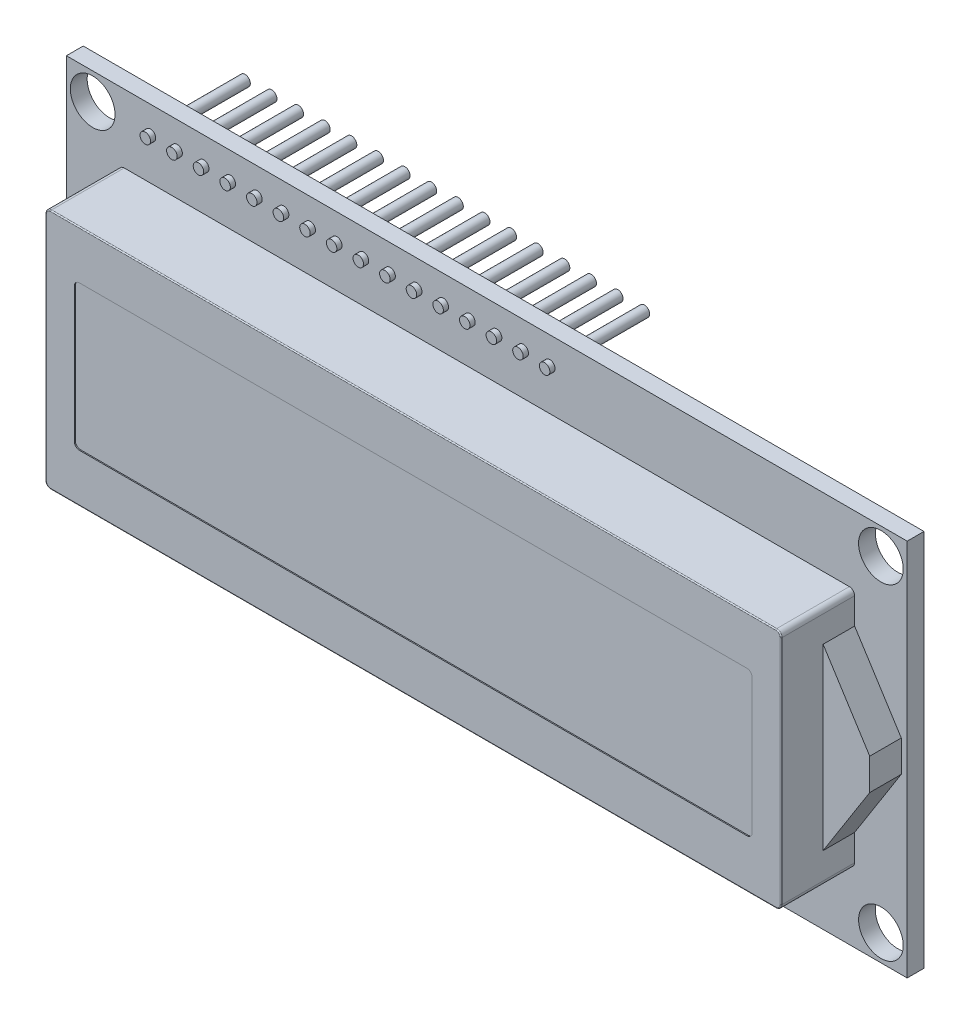
SolidWorks part; units mm, degrees
ref_plane "Alzado" through (0, 0, 0) normal (0, 0, 1) x (1, 0, 0)
ref_plane "Planta" through (0, 0, 0) normal (0, 1, 0) x (1, 0, 0)
ref_plane "Vista lateral" through (0, 0, 0) normal (1, 0, 0) x (0, 0, -1)
sketch "Croquis1" plane through (0, 0, 0) normal (0, 0, 1) x (1, 0, 0)
  line L1 (0, 0) -> (80, 0)
  line L2 (0, 0) -> (0, 36)
  line L3 (0, 36) -> (80, 36)
  line L4 (80, 0) -> (80, 36)
  circle A0 centre (2.5, 33.46) radius 2.125
  circle A1 centre (77.5, 33.51) radius 2.125
  circle A2 centre (77.5, 2.49) radius 2.125
  circle A3 centre (2.5, 2.49) radius 2.125
  circle A4 centre (8, 33.46) radius 0.5
  circle A5 centre (10.5333, 33.46) radius 0.5
  circle A6 centre (13.0667, 33.46) radius 0.5
  circle A7 centre (15.6, 33.46) radius 0.5
  circle A8 centre (18.1333, 33.46) radius 0.5
  circle A9 centre (20.6667, 33.46) radius 0.5
  circle A10 centre (23.2, 33.46) radius 0.5
  circle A11 centre (25.7333, 33.46) radius 0.5
  circle A12 centre (28.2666, 33.46) radius 0.5
  circle A13 centre (30.8, 33.46) radius 0.5
  circle A14 centre (33.3333, 33.46) radius 0.5
  circle A15 centre (35.8666, 33.46) radius 0.5
  circle A16 centre (38.4, 33.46) radius 0.5
  circle A17 centre (40.9333, 33.46) radius 0.5
  circle A18 centre (43.4666, 33.46) radius 0.5
  circle A19 centre (45.9999, 33.46) radius 0.5
  dimension "D3" = 4.25
  dimension "D7" = 1
  dimension "D1" = 80
  dimension "D2" = 36
  dimension "D5" = 2.5
  dimension "D6" = 8
  dimension "D8" = 2.54
  dimension "D9" = 16
extrude "Saliente-Extruir1" add sketch "Croquis1" along normal blind 1.6
sketch "Croquis2" plane through (0, 0, 1.6) normal (0, 0, 1) x (1, 0, 0)
  line L0 (0, 36) -> (0, 0) construction
  line L1 (5, 29.5) -> (75, 29.5)
  line L2 (5, 29.5) -> (5, 6.5)
  line L3 (5, 6.5) -> (75, 6.5)
  line L4 (75, 29.5) -> (75, 6.5)
  line L5 (80, 36) -> (0, 36) construction
  dimension "D1" = 70
  dimension "D2" = 5
  dimension "D3" = 6.5
  dimension "D4" = 23
extrude "Saliente-Extruir2" add sketch "Croquis2" along normal blind 7
sketch "Croquis3" plane through (0, 0, 1.6) normal (0, 0, 1) x (1, 0, 0)
  line L0 (75, 26.5) -> (79.4378, 19.5)
  line L1 (75, 6.5) -> (75, 29.5) construction
  line L2 (79.4378, 19.5) -> (79.4378, 16.5)
  line L3 (79.4378, 16.5) -> (75, 9.5)
  line L4 (75, 26.5) -> (75, 9.5)
  line L5 (75, 9.5) -> (74.9994, 9.3543)
  line M27 (75, 29.5) -> (75, 6.5)
  dimension "D1" = 3
  dimension "D2" = 3
  dimension "D3" = 7
  dimension "D4" = 7
extrude "Saliente-Extruir3" add sketch "Croquis3" along normal blind 3 contours L3 L2 L0 M27
sketch "Croquis4" plane through (0, 0, 1.6) normal (0, 0, 1) x (1, 0, 0)
  text T0 "1                                                 16" font "Century Gothic" height in points 8
sketch "Croquis6" plane through (0, 0, 1.6) normal (0, 0, 1) x (1, 0, 0)
  circle A0 centre (8, 33.46) radius 0.5
  circle A1 centre (10.5333, 33.46) radius 0.5
  circle A2 centre (13.0667, 33.46) radius 0.5
  circle A3 centre (15.6, 33.46) radius 0.5
  circle A4 centre (18.1333, 33.46) radius 0.5
  circle A5 centre (20.6667, 33.46) radius 0.5
  circle A6 centre (23.2, 33.46) radius 0.5
  circle A7 centre (25.7333, 33.46) radius 0.5
  circle A8 centre (28.2666, 33.46) radius 0.5
  circle A9 centre (30.8, 33.46) radius 0.5
  circle A10 centre (33.3333, 33.46) radius 0.5
  circle A11 centre (35.8666, 33.46) radius 0.5
  circle A12 centre (38.4, 33.46) radius 0.5
  circle A13 centre (40.9333, 33.46) radius 0.5
  circle A14 centre (43.4666, 33.46) radius 0.5
  circle A15 centre (45.9999, 33.46) radius 0.5
extrude "Saliente-Extruir4" add sketch "Croquis6" along normal blind 0.5 and the other way blind 9
sketch "Croquis7" plane through (0, 0, 8.6) normal (0, 0, 1) x (1, 0, 0)
  line L0 (5, 6.5) -> (75, 6.5) construction
  line L1 (8.25, 24.9) -> (71.75, 24.9)
  line L2 (7.75, 24.4) -> (7.75, 11.6)
  line L3 (8.25, 11.1) -> (71.75, 11.1)
  line L4 (72.25, 24.4) -> (72.25, 11.6)
  line L5 (5, 29.5) -> (5, 6.5) construction
  arc A0 (71.75, 11.1) -> (72.25, 11.6) centre (71.75, 11.6) ccw
  arc A1 (72.25, 24.4) -> (71.75, 24.9) centre (71.75, 24.4) ccw
  arc A2 (7.75, 11.6) -> (8.25, 11.1) centre (8.25, 11.6) ccw
  arc A3 (7.75, 24.4) -> (8.25, 24.9) centre (8.25, 24.4) cw
  point P4 (40, 24.9)
  point P7 (40, 6.5)
  point P8 (7.75, 18)
  point P11 (5, 18)
  point P14 (72.25, 11.1)
  point P19 (7.75, 11.1)
  point P22 (7.75, 24.9)
  dimension "D3" = 0.5
  dimension "D1" = 64.5
  dimension "D2" = 13.8
extrude "Cortar-Extruir1" cut sketch "Croquis7" against normal blind 0.1
fillet "Redondeo1" radius 0.5 4 edges at (5, 6.5, 5.1) (5, 29.5, 5.1) (75, 29.5, 5.1) (75, 6.5, 5.1)
fillet "Fillet2" radius 0.1 8 edges at (74.8536, 29.3536, 8.6) (75, 18, 8.6) (74.8536, 6.6464, 8.6) (40, 6.5, 8.6) (5.1464, 6.6464, 8.6) (5, 18, 8.6) (5.1464, 29.3536, 8.6) (40, 29.5, 8.6)
